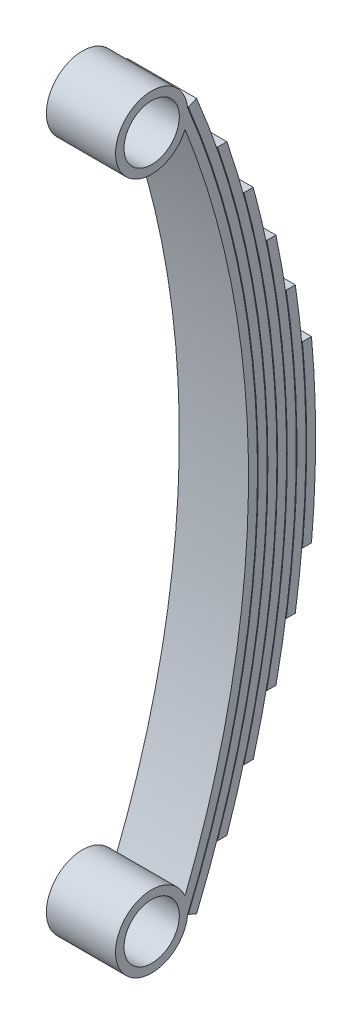
SolidWorks part; units mm, degrees
ref_plane "Front Plane" through (0, 0, 0) normal (1, 0, 0) x (0, 1, 0)
ref_plane "Top Plane" through (0, 0, 0) normal (0, 0, 1) x (0, 1, 0)
ref_plane "Right Plane" through (0, 0, 0) normal (0, 1, 0) x (-1, 0, 0)
sketch "Sketch1" plane through (0, 0, 0) normal (1, 0, 0) x (0, 1, 0)
  arc A0 (-500, 100) -> (500, 100) centre (0, 1300) ccw
  arc A1 (-505, 88) -> (505, 88) centre (0, 1300) ccw
  circle A2 centre (-500, 140) radius 40
  circle A3 centre (-500, 140) radius 52.2398
  circle A4 centre (500, 140) radius 40
  circle A5 centre (500, 140) radius 52.2398
  point P3 (0, 0)
  point P14 (0, 0)
  point P15 (0, 0)
  point P16 (0, 0)
  dimension "D2" = 1300
  dimension "D4" = 80
  dimension "D5" = 80
  dimension "D3" = 13
extrude "Boss-Extrude1" add sketch "Sketch1" along normal mid plane 100
sketch "Sketch2" plane through (50, 0, 0) normal (1, 0, 0) x (0, 1, 0)
  line L0 (-505.3846, 87.0769) -> (-510.3846, 75.0769)
  line L1 (505.3846, 87.0769) -> (510.3846, 75.0769)
  arc A2 (-510.3846, 75.0769) -> (510.3846, 75.0769) centre (0, 1300) ccw
  arc A3 (-510.3846, 75.0769) -> (510.3846, 75.0769) centre (0, 1300) ccw
  arc A5 (-505.3846, 87.0769) -> (505.3846, 87.0769) centre (0, 1300) ccw
  arc A6 (-505.3846, 87.0769) -> (505.3846, 87.0769) centre (0, 1300) ccw
  dimension "D1" = 14
  dimension "D2" = 1
extrude "Boss-Extrude2" add sketch "Sketch2" against normal blind 100 separate body
sketch "Sketch3" plane through (50, 0, 0) normal (1, 0, 0) x (0, 1, 0)
  line L0 (0, 0) -> (0, 191.9127) construction
  line L1 (-434.2692, 191.9127) -> (-434.2692, -137.1485) construction
  line L2 (434.2692, 191.9127) -> (434.2692, -137.1485) construction
  line L3 (434.2692, 45.0123) -> (434.2692, 31.2639)
  line L4 (-434.2692, 45.0123) -> (-434.2692, 31.2639)
  arc A2 (-510.7692, 74.1538) -> (510.7692, 74.1538) centre (0, 1300) ccw
  arc A3 (-434.2692, 45.0123) -> (434.2692, 45.0123) centre (0, 1300) ccw
  arc A5 (-515.7692, 62.1538) -> (515.7692, 62.1538) centre (0, 1300) ccw
  arc A6 (-434.2692, 31.2639) -> (434.2692, 31.2639) centre (0, 1300) ccw
  dimension "D3" = 76.5
  dimension "D1" = 1
  dimension "D2" = 14
extrude "Boss-Extrude3" add sketch "Sketch3" against normal blind 100 separate body
sketch "Sketch4" plane through (50, 0, 0) normal (1, 0, 0) x (0, 1, 0)
  line L0 (0, 0) -> (0, 226.8381) construction
  line L1 (-358.0931, -84.8416) -> (-358.0931, 182.3125) construction
  line L2 (-358.0931, -6.8261) -> (-358.0931, 6.6581)
  line L3 (358.0931, -6.8261) -> (358.0931, 6.6581)
  line L4 (358.0931, -84.8416) -> (358.0931, 182.3125) construction
  arc A2 (-438.803, 18.0184) -> (438.803, 18.0184) centre (0, 1300) ccw
  arc A3 (-358.0931, -6.8261) -> (358.0931, -6.8261) centre (0, 1300) ccw
  arc A5 (-434.5931, 30.3178) -> (434.5931, 30.3178) centre (0, 1300) ccw
  arc A6 (-358.0931, 6.6581) -> (358.0931, 6.6581) centre (0, 1300) ccw
  dimension "D3" = 76.5
  dimension "D1" = 14
  dimension "D2" = 1
extrude "Boss-Extrude4" add sketch "Sketch4" against normal blind 100 separate body
sketch "Sketch5" plane through (50, 0, 0) normal (1, 0, 0) x (0, 1, 0)
  line L0 (0, 0) -> (0, 232.702) construction
  line L1 (-281.8573, -242.7905) -> (-281.8573, 198.9048) construction
  line L2 (-281.8573, -39.6706) -> (-281.8573, -26.3832)
  line L3 (281.8573, -39.6706) -> (281.8573, -26.3832)
  arc A2 (-358.3573, -7.7905) -> (358.3573, -7.7905) centre (0, 1300) ccw
  arc A3 (-281.8573, -26.3832) -> (281.8573, -26.3832) centre (0, 1300) ccw
  arc A5 (-361.7929, -20.3283) -> (361.7929, -20.3283) centre (0, 1300) ccw
  arc A6 (-281.8573, -39.6706) -> (281.8573, -39.6706) centre (0, 1300) ccw
  dimension "D3" = 76.5
  dimension "D1" = 1
  dimension "D2" = 14
extrude "Boss-Extrude5" add sketch "Sketch5" against normal blind 100 separate body
sketch "Sketch6" plane through (50, 0, 0) normal (1, 0, 0) x (0, 1, 0)
  line L2 (0, 0) -> (0, 302.4941) construction
  line L3 (-205.5632, -217.8084) -> (-205.5632, 214.4842) construction
  line L4 (-205.5632, -54.4902) -> (-205.5632, -67.6377)
  line L5 (205.5632, -54.4902) -> (205.5632, -67.6377)
  arc A4 (-284.7397, -53.3707) -> (284.7397, -53.3707) centre (0, 1300) ccw
  arc A5 (-205.5632, -67.6377) -> (205.5632, -67.6377) centre (0, 1300) ccw
  arc A6 (-479.8517, 91.802) -> (479.8517, 91.802) centre (0, 1300) ccw construction
  arc A7 (-282.0632, -40.6492) -> (282.0632, -40.6492) centre (0, 1300) ccw
  arc A8 (-205.5632, -54.4902) -> (205.5632, -54.4902) centre (0, 1300) ccw
  dimension "D3" = 76.5
  dimension "D1" = 14
  dimension "D2" = 1
extrude "Boss-Extrude6" add sketch "Sketch6" against normal blind 100 separate body
sketch "Sketch7" plane through (50, 0, 0) normal (1, 0, 0) x (0, 1, 0)
  line L2 (0, 0) -> (0, 260.2973) construction
  line L3 (-129.2119, -141.2281) -> (-129.2119, 175.1979) construction
  line L4 (-129.2119, -77.9551) -> (-129.2119, -91.0116)
  line L5 (129.2119, -77.9551) -> (129.2119, -91.0116)
  arc A4 (-207.6441, -81.4821) -> (207.6441, -81.4821) centre (0, 1300) ccw
  arc A5 (-129.2119, -91.0116) -> (129.2119, -91.0116) centre (0, 1300) ccw
  arc A7 (-205.7119, -68.6265) -> (205.7119, -68.6265) centre (0, 1300) ccw
  arc A8 (-129.2119, -77.9551) -> (129.2119, -77.9551) centre (0, 1300) ccw
  dimension "D3" = 76.5
  dimension "D1" = 14
  dimension "D2" = 1
extrude "Boss-Extrude7" add sketch "Sketch7" against normal blind 100 separate body
